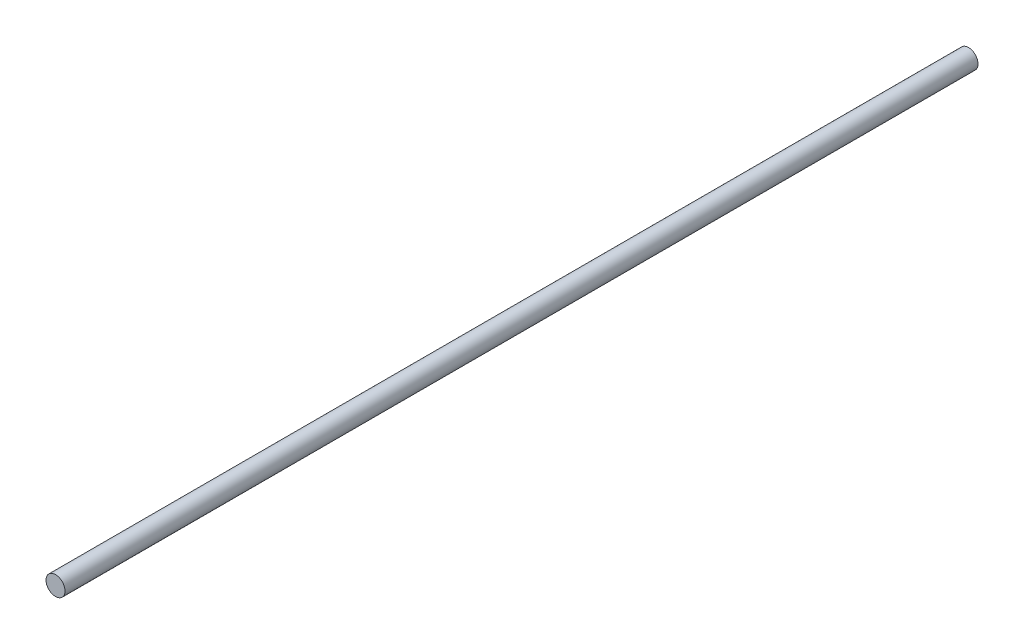
SolidWorks part; units mm, degrees
ref_plane "Front Plane" through (0, 0, 0) normal (0, 0, 1) x (1, 0, 0)
ref_plane "Top Plane" through (0, 0, 0) normal (0, 1, 0) x (1, 0, 0)
ref_plane "Right Plane" through (0, 0, 0) normal (1, 0, 0) x (0, 0, -1)
sketch "Sketch1" plane through (0, 0, 0) normal (0, 0, 1) x (1, 0, 0)
  circle A0 centre (0, 0) radius 6.35
  dimension "D1" = 12.7
extrude "Boss-Extrude1" add sketch "Sketch1" along normal blind 609.6
